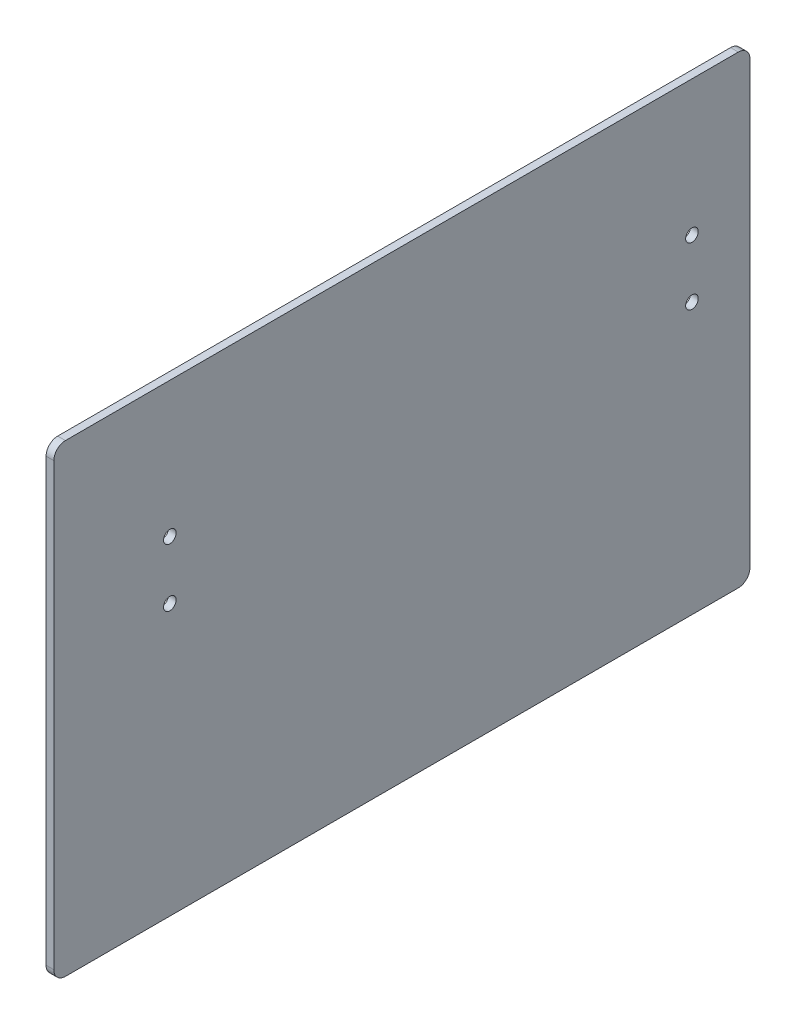
SolidWorks part; units mm, degrees
material "Acrylic (Medium-high impact)"
ref_plane "Front Plane" through (0, 0, 0) normal (0, 0, 1) x (1, 0, 0)
ref_plane "Top Plane" through (0, 0, 0) normal (0, 1, 0) x (1, 0, 0)
ref_plane "Right Plane" through (0, 0, 0) normal (1, 0, 0) x (0, 0, -1)
sketch "Sketch1" plane through (0, 0, 0) normal (1, 0, 0) x (0, 0, -1)
  line L1 (-180, -102.75) -> (180, -102.75)
  line L2 (-180, -102.75) -> (-180, 137.25)
  line L3 (-180, 137.25) -> (180, 137.25)
  line L4 (180, -102.75) -> (180, 137.25)
  line L5 (-180, -102.75) -> (180, 137.25) construction
  line L6 (-180, 137.25) -> (180, -102.75) construction
  point P0 (0, 17.25)
  dimension "D1" = 360
  dimension "D2" = 240
  dimension "D3" = 17.25
extrude "Boss-Extrude1" add sketch "Sketch1" along normal mid plane 4
fillet "Fillet3" radius 6 4 edges at (0, -102.75, 180) (0, -102.75, -180) (0, 137.25, -180) (0, 137.25, 180)
sketch "Sketch2" plane through (2, 0, 0) normal (1, 0, 0) x (0, 0, -1)
  line L0 (-180, 131.25) -> (-180, -96.75) construction
  line L1 (-120, 67.25) -> (150, 67.25)
  line L2 (-120, 67.25) -> (-120, 37.25)
  line L3 (-120, 37.25) -> (150, 37.25)
  line L4 (150, 67.25) -> (150, 37.25)
  line L5 (174, 137.25) -> (-174, 137.25) construction
  point P0 (-120, 67.25)
  point P1 (150, 37.25)
  point P2 (-120, 37.25)
  point P3 (150, 67.25)
  point P6 (-120, 52.25)
  dimension "D1" = 60
  dimension "D2" = 270
  dimension "D3" = 70
  dimension "D4" = 30
hole_wizard "Ø6.5 (6.5) Diameter Hole1" positions "Sketch2" profile "Sketch4" hole size "Ø6.5" standard "ANSI Metric" end condition through all
sketch "Sketch4" plane through (2, 67.25, 120) normal (0, 1, 0) x (0, 0, -1)
  line L0 (0, 0) -> (0, 4)
  line L1 (0, 4) -> (3.25, 4)
  line L2 (3.25, 4) -> (3.25, 0)
  line L5 (3.25, 0) -> (0, 0)
  line L11 (0, -6.35) -> (0, 107.95) construction
  dimension "Thru Hole Dia." = 6.5
  dimension "Thru Hole Depth" = 4
